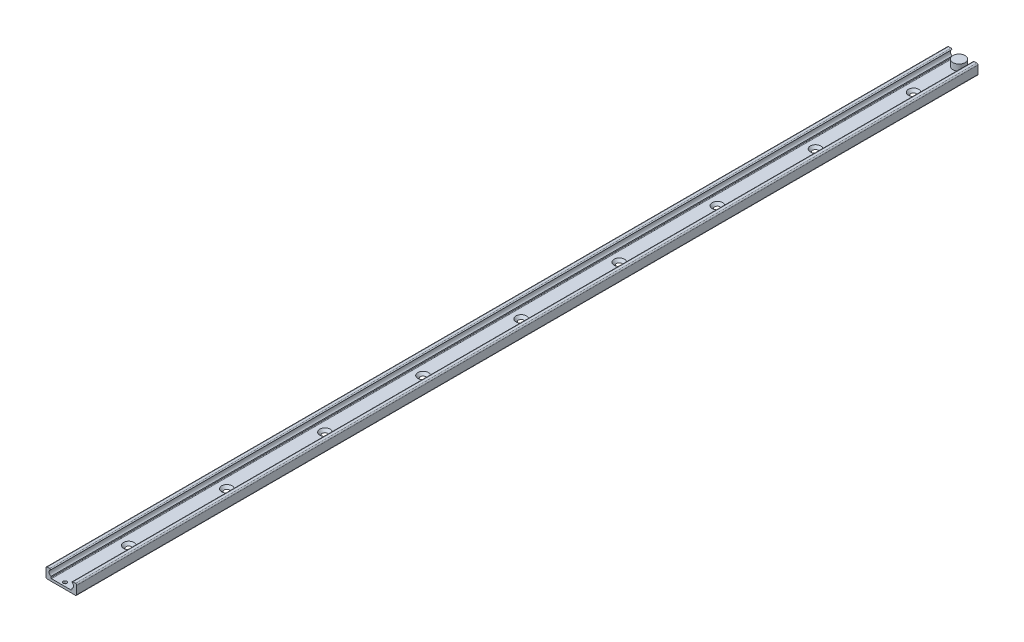
SolidWorks part; units mm, degrees
material "1060 合金"
ref_plane "正面" through (0, 0, 0) normal (0, 0, 1) x (1, 0, 0)
ref_plane "平面" through (0, 0, 0) normal (0, 1, 0) x (1, 0, 0)
ref_plane "右側面" through (0, 0, 0) normal (1, 0, 0) x (0, 0, -1)
ref_plane "平面1" through (0, 0, 720) normal (0, 0, 1) x (1, 0, 0)
sketch "ｽｹｯﾁ1" plane through (0, 0, 720) normal (0, 0, 1) x (1, 0, 0)
  line L0 (8.5, 3.4087) -> (8.5, 2)
  line L1 (8.5, 2) -> (-8.5, 2)
  line L2 (-8.5, 2) -> (-8.5, 3.4087)
  line L3 (-9.5, 8.5) -> (-12.5, 8.5)
  line L4 (-12.5, 8.5) -> (-12.5, 0)
  line L5 (-12.5, 0) -> (12.5, 0)
  line L6 (12.5, 0) -> (12.5, 8.5)
  line L7 (12.5, 8.5) -> (9.5, 8.5)
  arc A0 (8.6036, 7.9432) -> (8.5, 3.4087) centre (7.5, 5.7) cw
  arc A1 (-8.5, 3.4087) -> (-8.6036, 7.9432) centre (-7.5, 5.7) cw
  arc A2 (-8.6036, 7.9432) -> (-9.5, 8.5) centre (-9.5, 7.5) ccw
  arc A3 (9.5, 8.5) -> (8.6036, 7.9432) centre (9.5, 7.5) ccw
extrude "ﾎﾞｽ - 押し出し1" add sketch "ｽｹｯﾁ1" against normal blind 720
sketch "ｽｹｯﾁ3" plane through (0, 2, 0) normal (0, 1, 0) x (-1, 0, 0)
  circle A0 centre (0, 3) radius 5
extrude "ﾎﾞｽ - 押し出し3" add sketch "ｽｹｯﾁ3" along normal blind 5
hole_wizard "穴1" positions "ｽｹｯﾁ5" profile "ｽｹｯﾁ4" legacy
sketch "ｽｹｯﾁ5" plane through (0, 2, 0) normal (0, 1, 0) x (1, 0, 0)
  point P0 (0, -40)
  point P1 (0, -680)
  point P2 (0, -600)
  point P3 (0, -520)
  point P4 (0, -440)
  point P5 (0, -360)
  point P6 (0, -280)
  point P7 (0, -200)
  point P8 (0, -120)
sketch "ｽｹｯﾁ4" plane through (0, 2, 40) normal (1, 0, 0) x (0, 0, 1)
  line L0 (0, 0) -> (0, 2)
  line L1 (0, 2) -> (2.25, 2)
  line L2 (2.25, 2) -> (4.25, 0)
  line L3 (4.25, 0) -> (0, 0)
  line L4 (0, 110) -> (0, -10) construction
  dimension "副次直径" = 4.5
  dimension "深さ" = 2
  dimension "主要直径" = 8.5
fillet "ﾌｨﾚｯﾄ1" radius 0.5 2 edges at (-8.5, 2, 360) (8.5, 2, 360)
fillet "ﾌｨﾚｯﾄ2" radius 1 4 edges at (12.5, 0, 360) (12.5, 8.5, 360) (-12.5, 8.5, 360) (-12.5, 0, 360)
sketch "ｽｹｯﾁ6" plane through (0, 0, 720) normal (0, 0, 1) x (1, 0, 0)
  line L1 (-15.9751, -10.7593) -> (15.9751, -10.7593)
  line L2 (-15.9751, -10.7593) -> (-15.9751, 10.7593)
  line L3 (-15.9751, 10.7593) -> (15.9751, 10.7593)
  line L4 (15.9751, -10.7593) -> (15.9751, 10.7593)
  line L5 (-15.9751, -10.7593) -> (15.9751, 10.7593) construction
  line L6 (-15.9751, 10.7593) -> (15.9751, -10.7593) construction
  point P0 (0, 0)
  line M1 (-11.5, 0) -> (11.5, 0)
  arc M2 (11.5, 0) -> (12.5, 1) centre (11.5, 1) ccw
  line M3 (12.5, 1) -> (12.5, 7.5)
  arc M4 (12.5, 7.5) -> (11.5, 8.5) centre (11.5, 7.5) ccw
  line M5 (11.5, 8.5) -> (9.5, 8.5)
  arc M6 (9.5, 8.5) -> (8.6036, 7.9432) centre (9.5, 7.5) ccw
  arc M7 (8.6036, 7.9432) -> (8.5, 3.4087) centre (7.5, 5.7) cw
  line M8 (8.5, 3.4087) -> (8.5, 2.5)
  arc M9 (8.5, 2.5) -> (8, 2) centre (8, 2.5) cw
  line M10 (8, 2) -> (-8, 2)
  arc M11 (-8, 2) -> (-8.5, 2.5) centre (-8, 2.5) cw
  line M12 (-8.5, 2.5) -> (-8.5, 3.4087)
  arc M13 (-8.5, 3.4087) -> (-8.6036, 7.9432) centre (-7.5, 5.7) cw
  arc M14 (-8.6036, 7.9432) -> (-9.5, 8.5) centre (-9.5, 7.5) ccw
  line M15 (-9.5, 8.5) -> (-11.5, 8.5)
  arc M16 (-11.5, 8.5) -> (-12.5, 7.5) centre (-11.5, 7.5) ccw
  line M17 (-12.5, 7.5) -> (-12.5, 1)
  arc M18 (-12.5, 1) -> (-11.5, 0) centre (-11.5, 1) ccw
extrude "ﾎﾞｽ - 押し出し4" add sketch "ｽｹｯﾁ6" along normal blind 15 contours M18 M1 M2 M3 M4 M5 M6 M7 M8 M9 M10 M11 M12 M13 M14 M15 M16 M17
sketch "ｽｹｯﾁ7" plane through (0, 2, 0) normal (0, 1, 0) x (1, 0, 0)
  line L0 (0, -735) -> (0, -732) construction
  line L1 (8, -735) -> (-8, -735) construction
  circle A0 centre (0, -732) radius 1.5
  dimension "D2" = 3
  dimension "D1" = 3
extrude "ｶｯﾄ - 押し出し1" cut sketch "ｽｹｯﾁ7" against normal through all
